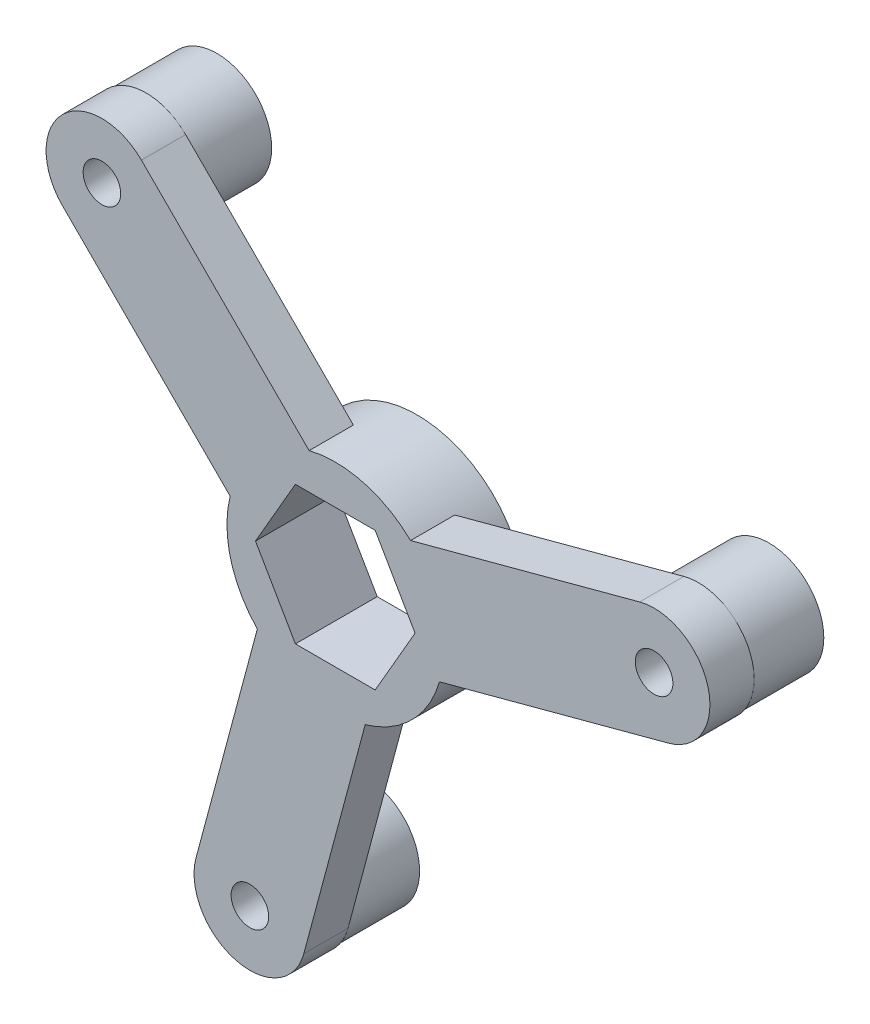
SolidWorks part; units mm, degrees
ref_plane "Front Plane" through (0, 0, 0) normal (0, 0, 1) x (1, 0, 0)
ref_plane "Top Plane" through (0, 0, 0) normal (0, 1, 0) x (1, 0, 0)
ref_plane "Right Plane" through (0, 0, 0) normal (1, 0, 0) x (0, 0, -1)
sketch "S01 - Hex coupling boss" plane through (0, 0, 0) normal (0, 0, 1) x (1, 0, 0)
  circle A0 centre (0, 0) radius 9.8
  dimension "D1" = 19.6
extrude "01 - Hex coupling boss" add sketch "S01 - Hex coupling boss" along normal blind 7.4 from offset 3
sketch "S02 - Drive spoke 1" plane through (0, 0, 0) normal (0, 0, 1) x (1, 0, 0)
  line L0 (5.9012, 6.8094) -> (27.5258, 12.6037)
  line L1 (30.1399, 2.8478) -> (8.5153, -2.9465)
  arc A0 (27.5258, 12.6037) -> (30.1399, 2.8478) centre (28.8329, 7.7257) cw
  arc A1 (8.5153, -2.9465) -> (5.9012, 6.8094) centre (7.2082, 1.9314) cw
  dimension "D1" = 5.05
  dimension "D2" = 5.05
  dimension "D3" = 5.9012
  dimension "D4" = 7.2082
  dimension "D5" = 8.5153
  dimension "D6" = 27.5258
  dimension "D7" = 28.8329
  dimension "D8" = 30.1399
  dimension "D9" = 1.9314
  dimension "D10" = 2.8478
extrude "02 - Drive spoke 1" add sketch "S02 - Drive spoke 1" along normal blind 4 from offset 6.4
sketch "S03 - Flange standoff 1" plane through (0, 0, 0) normal (0, 0, 1) x (1, 0, 0)
  circle A0 centre (28.8329, 7.7257) radius 4.95
  dimension "D1" = 9.9
  dimension "D2" = 28.8329
  dimension "D3" = 7.7257
extrude "03 - Flange standoff 1" add sketch "S03 - Flange standoff 1" along normal blind 6.4
sketch "S04 - Drive spoke 2" plane through (0, 0, 0) normal (0, 0, 1) x (1, 0, 0)
  line L0 (-8.8477, 1.7059) -> (-24.678, 17.5362)
  line L1 (-17.5362, 24.678) -> (-1.7059, 8.8477)
  arc A0 (-24.678, 17.5362) -> (-17.5362, 24.678) centre (-21.1071, 21.1071) cw
  arc A1 (-1.7059, 8.8477) -> (-8.8477, 1.7059) centre (-5.2768, 5.2768) cw
  dimension "D1" = 5.05
  dimension "D2" = 5.05
  dimension "D3" = 1.7059
  dimension "D4" = 5.2768
  dimension "D5" = 8.8477
  dimension "D6" = 17.5362
  dimension "D7" = 21.1071
  dimension "D8" = 24.678
  dimension "D9" = 1.7059
  dimension "D10" = 17.5362
extrude "04 - Drive spoke 2" add sketch "S04 - Drive spoke 2" along normal blind 4 from offset 6.4
sketch "S05 - Flange standoff 2" plane through (0, 0, 0) normal (0, 0, 1) x (1, 0, 0)
  circle A0 centre (-21.1071, 21.1071) radius 4.95
  dimension "D1" = 9.9
  dimension "D2" = 21.1071
  dimension "D3" = 21.1071
extrude "05 - Flange standoff 2" add sketch "S05 - Flange standoff 2" along normal blind 6.4
sketch "S06 - Drive spoke 3" plane through (0, 0, 0) normal (0, 0, 1) x (1, 0, 0)
  line L0 (2.9465, -8.5153) -> (-2.8478, -30.1399)
  line L1 (-12.6037, -27.5258) -> (-6.8094, -5.9012)
  arc A0 (-2.8478, -30.1399) -> (-12.6037, -27.5258) centre (-7.7257, -28.8329) cw
  arc A1 (-6.8094, -5.9012) -> (2.9465, -8.5153) centre (-1.9314, -7.2082) cw
  dimension "D1" = 5.05
  dimension "D2" = 5.05
  dimension "D3" = 2.9465
  dimension "D4" = 1.9314
  dimension "D5" = 2.8478
  dimension "D6" = 6.8094
  dimension "D7" = 7.7257
  dimension "D8" = 12.6037
  dimension "D9" = 5.9012
  dimension "D10" = 27.5258
extrude "06 - Drive spoke 3" add sketch "S06 - Drive spoke 3" along normal blind 4 from offset 6.4
sketch "S07 - Flange standoff 3" plane through (0, 0, 0) normal (0, 0, 1) x (1, 0, 0)
  circle A0 centre (-7.7257, -28.8329) radius 4.95
  dimension "D1" = 9.9
  dimension "D2" = 7.7257
  dimension "D3" = 28.8329
extrude "07 - Flange standoff 3" add sketch "S07 - Flange standoff 3" along normal blind 6.4
sketch "S08 - Floating 12 mm AF drive socket" plane through (0, 0, 0) normal (0, 0, 1) x (1, 0, 0)
  line L0 (7.2169, 0) -> (3.6084, 6.25)
  line L1 (3.6084, 6.25) -> (-3.6084, 6.25)
  line L2 (-3.6084, 6.25) -> (-7.2169, 0)
  line L3 (-7.2169, 0) -> (-3.6084, -6.25)
  line L4 (-3.6084, -6.25) -> (3.6084, -6.25)
  line L5 (3.6084, -6.25) -> (7.2169, 0)
  dimension "D1" = 3.6084
  dimension "D2" = 7.2169
  dimension "D3" = 3.6084
  dimension "D4" = 7.2169
  dimension "D5" = 6.25
  dimension "D6" = 6.25
extrude "08 - Floating 12 mm AF drive socket" cut sketch "S08 - Floating 12 mm AF drive socket" along normal blind 10.6 from offset 0.1
sketch "S09 - Three shared through-fasteners" plane through (0, 0, 0) normal (0, 0, 1) x (1, 0, 0)
  circle A0 centre (28.8329, 7.7257) radius 1.7
  circle A1 centre (-21.1071, 21.1071) radius 1.7
  circle A2 centre (-7.7257, -28.8329) radius 1.7
  dimension "D1" = 3.4
  dimension "D2" = 3.4
  dimension "D3" = 3.4
  dimension "D4" = 28.8329
  dimension "D5" = 7.7257
  dimension "D6" = 21.1071
  dimension "D7" = 7.7257
  dimension "D8" = 21.1071
  dimension "D9" = 28.8329
extrude "09 - Three shared through-fasteners" cut sketch "S09 - Three shared through-fasteners" along normal blind 10.6 from offset 0.1
